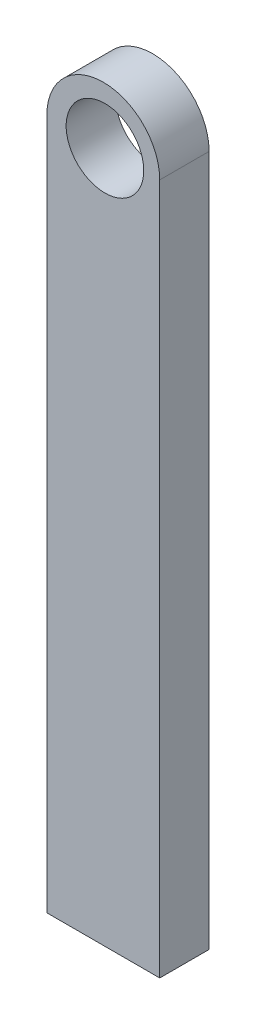
SolidWorks part; units mm, degrees
ref_plane "Front Plane" through (0, 0, 0) normal (0, 0, 1) x (1, 0, 0)
ref_plane "Top Plane" through (0, 0, 0) normal (0, 1, 0) x (1, 0, 0)
ref_plane "Right Plane" through (0, 0, 0) normal (1, 0, 0) x (0, 0, -1)
sketch "Sketch1" plane through (0, 0, 0) normal (0, 0, 1) x (1, 0, 0)
  line L0 (-17.2154, 33.3521) -> (-17.2154, -122.2229)
  line L1 (8.1846, 33.3521) -> (8.1846, -122.2229)
  line L3 (-17.2154, -122.2229) -> (8.1846, -122.2229)
  arc A0 (-17.2154, 33.3521) -> (8.1846, 33.3521) centre (-4.5154, 33.3521) cw
  dimension "D1" = 25.4
  dimension "D2" = 155.575
extrude "Boss-Extrude1" add sketch "Sketch1" along normal blind 11.1125 contours L1 L3 L0 A0
sketch "Sketch3" plane through (0, 0, 11.1125) normal (0, 0, 1) x (1, 0, 0)
  circle A0 centre (-4.1474, 33.3574) radius 8.7312
  arc A2 (8.1846, 33.3521) -> (-17.2154, 33.3521) centre (-4.5154, 33.3521) ccw construction
  point P5 (-4.5154, 46.0521)
  point P8 (8.1846, 31.0914)
  dimension "D1" = 17.4625
  dimension "D2" = 12.7
extrude "Cut-Extrude1" cut sketch "Sketch3" against normal through all
